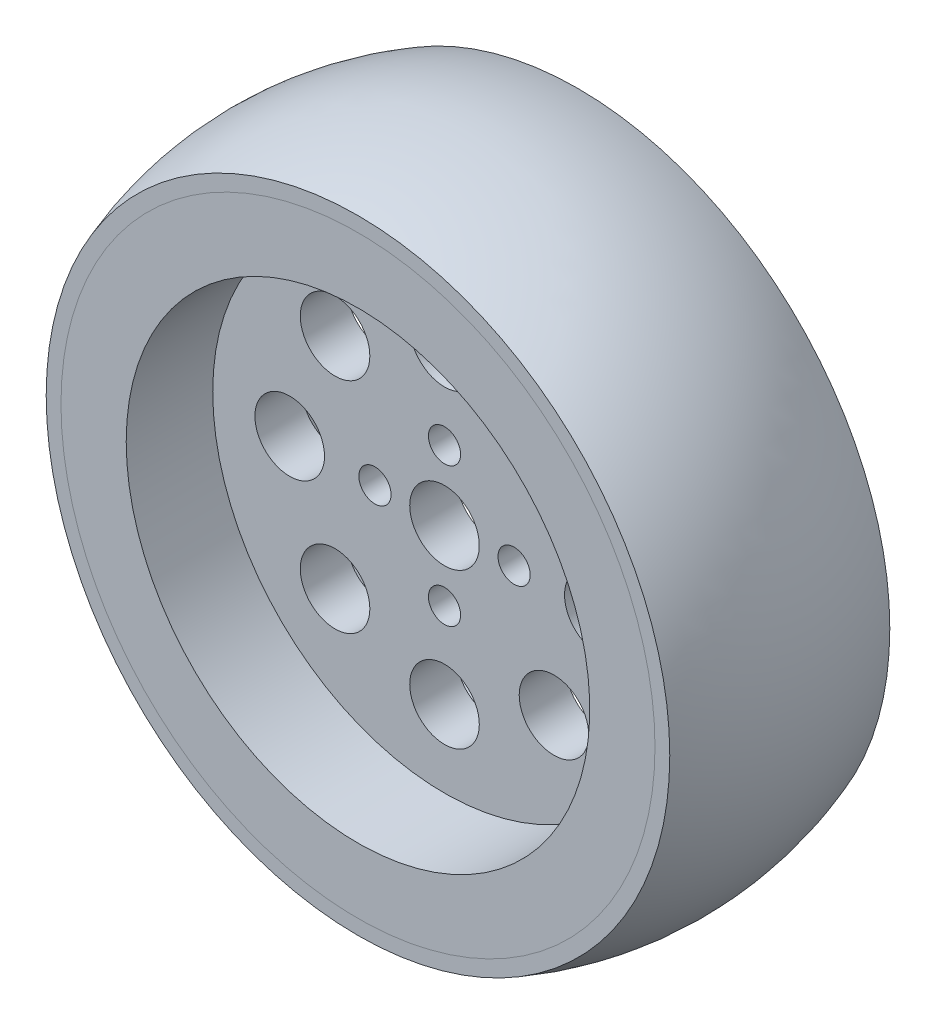
SolidWorks part; units mm, degrees
other "Defeature"
material "Nylon 6/10"
ref_plane "Front Plane" through (0, 0, 0) normal (0, 0, 1) x (1, 0, 0)
ref_plane "Top Plane" through (0, 0, 0) normal (0, 1, 0) x (1, 0, 0)
ref_plane "Right Plane" through (0, 0, 0) normal (1, 0, 0) x (0, 0, -1)
sketch "Sketch1" plane through (0, 0, 0) normal (0, 1, 0) x (1, 0, 0)
  line L0 (0, 12.65) -> (0, -12.65) construction
  line L1 (4, 2.7) -> (4, -2.7)
  line L2 (4, -2.7) -> (26.65, -2.7)
  line L3 (26.65, -2.7) -> (26.65, -12.65)
  line L4 (26.65, -12.65) -> (34.15, -12.65)
  line L5 (34.15, -12.65) -> (34.15, -10.65)
  line L6 (34.15, -10.65) -> (31.85, -10.65)
  line L7 (31.85, -10.65) -> (31.85, 10.65)
  line L8 (31.85, 10.65) -> (34.15, 10.65)
  line L9 (34.15, 10.65) -> (34.15, 12.65)
  line L10 (34.15, 12.65) -> (26.65, 12.65)
  line L11 (26.65, 12.65) -> (26.65, 2.7)
  line L12 (26.65, 2.7) -> (4, 2.7)
  point P3 (0, 0)
  point P6 (4, 0)
  point P17 (31.85, 0)
  dimension "D1" = 8
  dimension "D2" = 25.3
  dimension "D3" = 2
  dimension "D4" = 7.5
  dimension "D5" = 2.3
  dimension "D6" = 5.4
  dimension "D7" = 68.3
revolve "Revolve1" add sketch "Sketch1" angle 360 about L0
sketch "Sketch2" plane through (0, 0, 0) normal (0, 1, 0) x (1, 0, 0)
  line L0 (31.85, -10.65) -> (31.85, 10.65) construction
  line L1 (34.15, 10.65) -> (34.15, 12.65) construction
  line L2 (-34.15, 10.65) -> (34.15, 10.65) construction
  line L3 (34.15, -10.65) -> (-34.15, -10.65) construction
  line L4 (34.15, -12.65) -> (34.15, -10.65) construction
  line L5 (31.85, -10.65) -> (31.85, 10.65)
  line L6 (34.15, 10.65) -> (34.15, 12.65)
  line L7 (31.85, 10.65) -> (34.15, 10.65)
  line L8 (34.15, -10.65) -> (31.85, -10.65)
  line L9 (34.15, -12.65) -> (34.15, -10.65)
  line L10 (34.15, 12.65) -> (35.85, 12.65)
  line L11 (34.15, -12.65) -> (35.85, -12.65)
  line L12 (0, 0) -> (0, -12.65) construction
  line L13 (-34.15, -12.65) -> (34.15, -12.65) construction
  arc A0 (35.85, 12.65) -> (35.85, -12.65) centre (1.4144, 0) cw
  point P11 (38.1, 0)
  dimension "D1" = 76.2
  dimension "D2" = 1.7
revolve "Revolve2" add sketch "Sketch2" angle 360 about L12
sketch "Sketch3" plane through (0, 0, 0) normal (0, 0, 1) x (1, 0, 0)
  line L0 (-12.5865, 12.5865) -> (12.5865, -12.5865) construction
  line L1 (12.5865, 12.5865) -> (-12.5865, -12.5865) construction
  line L2 (0, -8) -> (0, 0) construction
  circle A0 centre (0, 0) radius 8 construction
  circle A1 centre (0, 0) radius 17.8 construction
  circle A2 centre (0, 8) radius 1.85
  circle A3 centre (8, 0) radius 1.85
  circle A4 centre (0, -8) radius 1.85
  circle A5 centre (-8, 0) radius 1.85
  circle A6 centre (0, 17.8) radius 4
  circle A7 centre (12.5865, 12.5865) radius 4
  circle A8 centre (17.8, 0) radius 4
  circle A9 centre (12.5865, -12.5865) radius 4
  circle A10 centre (0, -17.8) radius 4
  circle A11 centre (-12.5865, -12.5865) radius 4
  circle A12 centre (-17.8, 0) radius 4
  circle A13 centre (-12.5865, 12.5865) radius 4
  circle A14 centre (0, 0) radius 4 construction
  point P28 (0, 13.8)
  point P29 (0, 4)
  dimension "D1" = 8
  dimension "D2" = 3.7
  dimension "D3" = 16
  dimension "D4" = 45
  dimension "D5" = 9.8
extrude "Cut-Extrude1" cut sketch "Sketch3" against normal through all both and the other way through all
